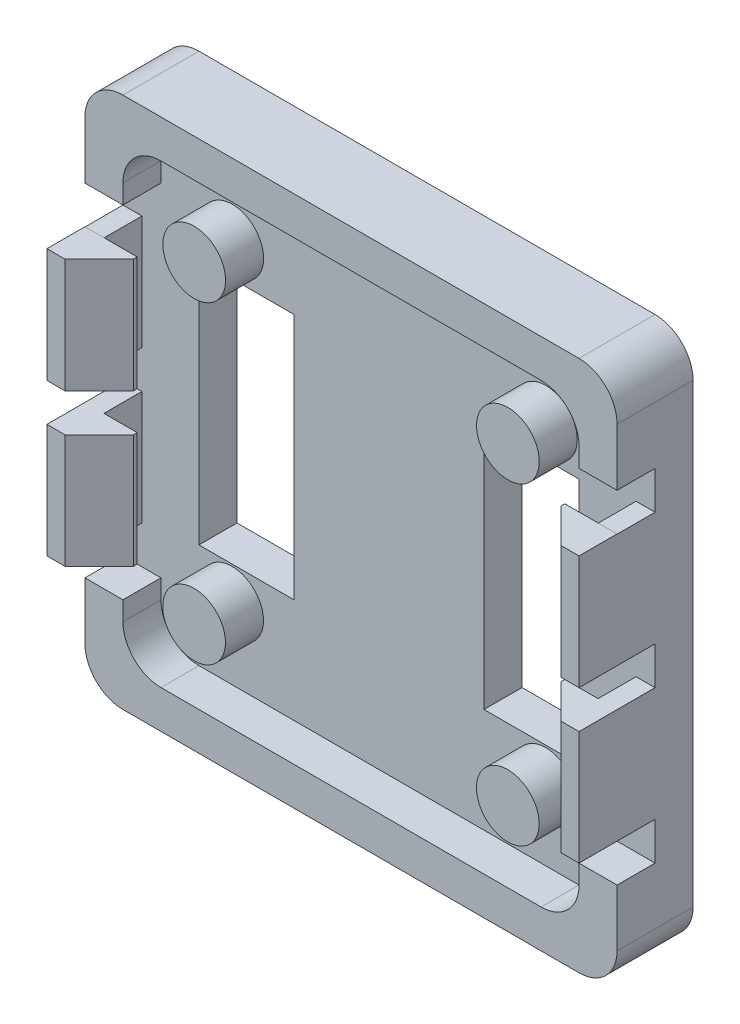
SolidWorks part; units mm, degrees
ref_plane "Plan de face" through (0, 0, 0) normal (0, 0, 1) x (1, 0, 0)
ref_plane "Plan de dessus" through (0, 0, 0) normal (0, 1, 0) x (1, 0, 0)
ref_plane "Plan de droite" through (0, 0, 0) normal (1, 0, 0) x (0, 0, -1)
sketch "Esquisse1" plane through (0, 0, 0) normal (0, 0, 1) x (1, 0, 0)
  line L1 (12, -14) -> (-12, -14)
  line L2 (14, -12) -> (14, 12)
  line L3 (12, 14) -> (-12, 14)
  line L4 (-14, -12) -> (-14, 12)
  line L5 (14, -14) -> (-14, 14) construction
  line L6 (14, 14) -> (-14, -14) construction
  arc A0 (-12, -14) -> (-14, -12) centre (-12, -12) cw
  arc A1 (12, -14) -> (14, -12) centre (12, -12) ccw
  arc A2 (14, 12) -> (12, 14) centre (12, 12) ccw
  arc A3 (-12, 14) -> (-14, 12) centre (-12, 12) ccw
  point P0 (0, 0)
  dimension "D2" = 2
  dimension "D1" = 28
extrude "Boss.-Extru.1" add sketch "Esquisse1" along normal blind 4
sketch "Esquisse2" plane through (0, 0, 4) normal (0, 0, 1) x (1, 0, 0)
  line L0 (-14, 12) -> (-14, -12) construction
  line L1 (-10, -12) -> (10, -12)
  line L2 (-12, -10) -> (-12, -9)
  line L3 (-10, 12) -> (10, 12)
  line L4 (12, -10) -> (12, -9)
  line L5 (-12, -12) -> (12, 12) construction
  line L6 (-12, 12) -> (12, -12) construction
  line L7 (-14, 8.9885) -> (-12, 8.9885)
  line L8 (-14, 8.9885) -> (-14, 6.9885)
  line L11 (-1000, -0.0058) -> (49000, -0.0058) construction
  line L14 (-14, -9) -> (-12, -9)
  line L15 (-14, -9) -> (-14, -7)
  line L16 (-12, 8.9885) -> (-12, 10)
  line L18 (-14, 6.9885) -> (-13, 6.9885)
  line L19 (-13, 6.9885) -> (-13, 0.9942)
  line L20 (-13, -7) -> (-14, -7)
  line L21 (0, -1000) -> (0, 49000) construction
  line L22 (14, 8.9885) -> (12, 8.9885)
  line L23 (14, 8.9885) -> (14, 6.9885)
  line L24 (14, 6.9885) -> (13, 6.9885)
  line L25 (13, 6.9885) -> (13, 0.9942)
  line L26 (13, -7) -> (14, -7)
  line L27 (14, -9) -> (14, -7)
  line L28 (14, -9) -> (12, -9)
  line L29 (12, 8.9885) -> (12, 10)
  line L30 (-13, -1.0058) -> (-13, -7)
  line L31 (-13, 0.9942) -> (-14, 0.9942)
  line L33 (-13, -1.0058) -> (-14, -1.0058)
  line L34 (-14, 0.9942) -> (-14, -1.0058)
  line L35 (13, -1.0058) -> (14, -1.0058)
  line L36 (14, 0.9942) -> (14, -1.0058)
  line L37 (13, 0.9942) -> (14, 0.9942)
  line L38 (13, -1.0058) -> (13, -7)
  arc A0 (-10, -12) -> (-12, -10) centre (-10, -10) cw
  arc A1 (10, -12) -> (12, -10) centre (10, -10) ccw
  arc A2 (10, 12) -> (12, 10) centre (10, 10) cw
  arc A3 (-12, 10) -> (-10, 12) centre (-10, 10) cw
  circle A4 centre (-8.25, 8.25) radius 1.65
  circle A6 centre (8.2558, 8.2442) radius 1.65
  circle A7 centre (8.25, -8.2615) radius 1.65
  circle A8 centre (-8.2558, -8.2558) radius 1.65
  point P0 (0, 0)
  point P29 (0, -0.0058)
  dimension "D3" = 2
  dimension "D4" = 3.3
  dimension "D5" = 8.25
  dimension "D1" = 24
  dimension "D2" = 24
  dimension "D6" = 8.25
  dimension "D8" = 1
  dimension "D9" = 2
  dimension "D10" = 2
  dimension "D11" = 1
  dimension "D7" = 4
extrude "Enlèv. mat.-Extru.1" cut sketch "Esquisse2" against normal blind 2
sketch "Esquisse3" plane through (0, 0, 2) normal (0, 0, 1) x (1, 0, 0)
  line L5 (-1000, 0) -> (49000, 0) construction
  line L6 (-12, -9) -> (-12, -10) construction
  line L7 (-5, -6.5) -> (-10, -6.5)
  line L8 (-5, -6.5) -> (-5, 6.5)
  line L9 (-5, 6.5) -> (-10, 6.5)
  line L10 (-10, -6.5) -> (-10, 6.5)
  line L11 (-5, -6.5) -> (-10, 6.5) construction
  line L12 (-5, 6.5) -> (-10, -6.5) construction
  line L13 (0, -1000) -> (0, 49000) construction
  line L14 (5, 6.5) -> (10, 6.5)
  line L15 (10, -6.5) -> (10, 6.5)
  line L16 (5, -6.5) -> (10, -6.5)
  line L17 (5, -6.5) -> (5, 6.5)
  point P0 (-7.5, 0)
  dimension "D1" = 13
  dimension "D2" = 5
  dimension "D3" = 4.5
extrude "Enlèv. mat.-Extru.2" cut sketch "Esquisse3" against normal through all
sketch "Esquisse4" plane through (0, 0, 4) normal (0, 0, 1) x (1, 0, 0)
  line L0 (-11.25, -1.0058) -> (-11.25, -7)
  line L5 (-12, -9) -> (-12, -10) construction
  line L6 (-14, 7) -> (-11.25, 7)
  line L7 (-14, 7) -> (-14, 0.9942)
  line L8 (-14, -7) -> (-11.25, -7)
  line L9 (-11.25, 7) -> (-11.25, 0.9942)
  line L10 (-14, 12) -> (-14, 8.9885) construction
  line L11 (-14, 0.9942) -> (-11.25, 0.9942)
  line L13 (-14, -1.0058) -> (-11.25, -1.0058)
  line L15 (-14, -1.0058) -> (-14, -7)
  dimension "D1" = 0.75
  dimension "D2" = 14
  dimension "D3" = 7
  dimension "D4" = 2
extrude "Boss.-Extru.2" add sketch "Esquisse4" along normal blind 2
chamfer "Chanfrein3" distance 1.8 angle 45 2 edges at (-11.25, -4.0029, 6) (-11.25, 3.9971, 6)
mirror "Symétrie1" about plane through (0, 0, 0) normal (1, 0, 0) of "Chanfrein3", "Boss.-Extru.2"
